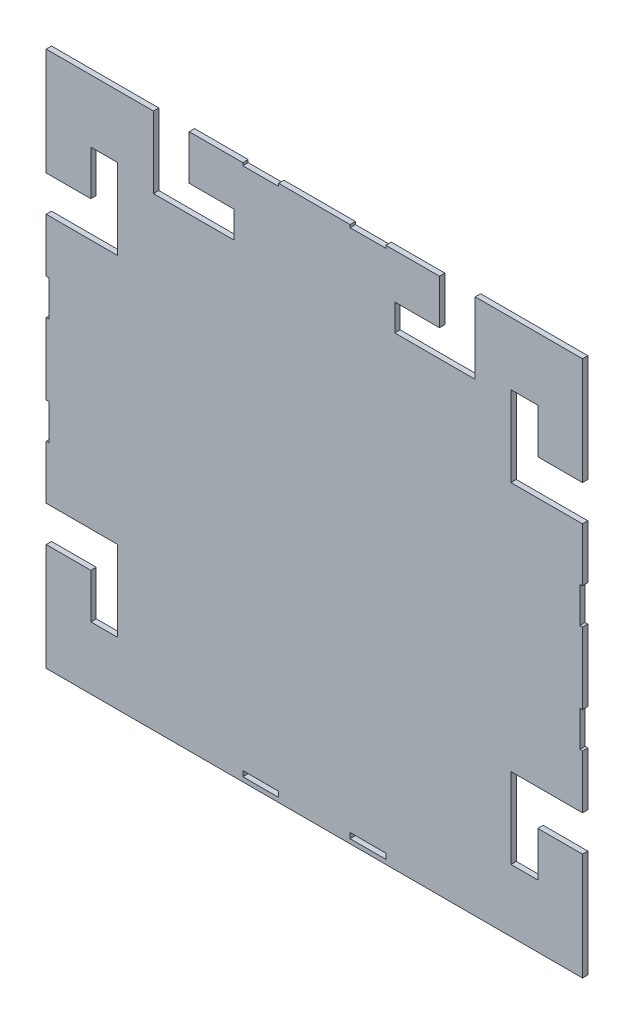
SolidWorks part; units mm, degrees
ref_plane "Plano frontal" through (0, 0, 0) normal (0, 0, 1) x (1, 0, 0)
ref_plane "Plano superior" through (0, 0, 0) normal (0, 1, 0) x (1, 0, 0)
ref_plane "Plano direito" through (0, 0, 0) normal (1, 0, 0) x (0, 0, -1)
sketch "Esboço2" plane through (0, 0, 0) normal (0, 0, 1) x (1, 0, 0)
  line L0 (-63.6451, -170) -> (-63.6451, -110)
  line L1 (-63.6451, -170) -> (236.3549, -170) construction
  line L2 (-63.6451, -170) -> (-63.6451, 130) construction
  line L3 (-63.6451, 130) -> (236.3549, 130) construction
  line L4 (236.3549, -170) -> (236.3549, 130) construction
  line L5 (-63.6451, -110) -> (-38.6451, -110)
  line L6 (-38.6451, -110) -> (-38.6451, -135)
  line L7 (-38.6451, -135) -> (-23.6451, -135)
  line L8 (-23.6451, -135) -> (-23.6451, -90)
  line L9 (-23.6451, -90) -> (-63.6451, -90)
  line L10 (-63.6451, -90) -> (-63.6451, -60)
  line L11 (236.3549, 20) -> (234.8549, 20)
  line L12 (236.3549, 0) -> (234.8549, 0)
  line L13 (234.8549, 0) -> (234.8549, 20)
  line L14 (-63.6451, -40) -> (-63.6451, 0)
  line L15 (236.3549, -40) -> (234.8549, -40)
  line L16 (236.3549, -60) -> (234.8549, -60)
  line L17 (234.8549, -60) -> (234.8549, -40)
  line L18 (-63.6451, 20) -> (-63.6451, 50)
  line L19 (-63.6451, 50) -> (-23.6451, 50)
  line L20 (-23.6451, 50) -> (-23.6451, 95)
  line L21 (-23.6451, 95) -> (-38.6451, 95)
  line L22 (-38.6451, 95) -> (-38.6451, 70)
  line L23 (-38.6451, 70) -> (-63.6451, 70)
  line L24 (-63.6451, 70) -> (-63.6451, 130)
  line L25 (-63.6451, 130) -> (-3.6451, 130)
  line L26 (176.3549, 130) -> (176.3549, 90)
  line L27 (176.3549, 90) -> (131.3549, 90)
  line L28 (131.3549, 90) -> (131.3549, 105)
  line L29 (156.3549, 130) -> (156.3549, 105)
  line L30 (156.3549, 105) -> (131.3549, 105)
  line L31 (16.3549, 130) -> (46.3549, 130)
  line L32 (16.3549, 130) -> (16.3549, 105)
  line L33 (16.3549, 105) -> (41.3549, 105)
  line L34 (41.3549, 105) -> (41.3549, 90)
  line L35 (41.3549, 90) -> (-3.6451, 90)
  line L36 (-3.6451, 90) -> (-3.6451, 130)
  line L37 (176.3549, 130) -> (236.3549, 130)
  line L38 (236.3549, 130) -> (236.3549, 70)
  line L39 (236.3549, 70) -> (211.3549, 70)
  line L40 (211.3549, 70) -> (211.3549, 95)
  line L41 (211.3549, 95) -> (196.3549, 95)
  line L42 (196.3549, 95) -> (196.3549, 50)
  line L43 (196.3549, 50) -> (236.3549, 50)
  line L44 (236.3549, 50) -> (236.3549, 20)
  line L45 (-63.6451, -60) -> (-62.1451, -60)
  line L46 (-62.1451, -60) -> (-62.1451, -40)
  line L47 (-63.6451, -40) -> (-62.1451, -40)
  line L48 (236.3549, 0) -> (236.3549, -40)
  line L49 (-63.6451, 0) -> (-62.1451, 0)
  line L50 (-62.1451, 0) -> (-62.1451, 20)
  line L51 (-62.1451, 20) -> (-63.6451, 20)
  line L52 (236.3549, -60) -> (236.3549, -90)
  line L53 (236.3549, -90) -> (196.3549, -90)
  line L54 (196.3549, -90) -> (196.3549, -135)
  line L55 (196.3549, -135) -> (211.3549, -135)
  line L56 (211.3549, -135) -> (211.3549, -110)
  line L57 (211.3549, -110) -> (236.3549, -110)
  line L58 (236.3549, -110) -> (236.3549, -170)
  line L59 (236.3549, -170) -> (-63.6451, -170)
  line L60 (126.3549, 130) -> (126.3549, 128.5)
  line L61 (126.3549, 128.5) -> (106.3549, 128.5)
  line L62 (106.3549, 128.5) -> (106.3549, 130)
  line L63 (66.3549, 130) -> (106.3549, 130)
  line L64 (66.3549, 130) -> (66.3549, 128.5)
  line L65 (66.3549, 128.5) -> (46.3549, 128.5)
  line L66 (46.3549, 128.5) -> (46.3549, 130)
  line L67 (126.3549, 130) -> (156.3549, 130)
  line L69 (46.3549, -167.5) -> (66.3549, -167.5)
  line L70 (46.3549, -167.5) -> (46.3549, -164.5)
  line L71 (46.3549, -164.5) -> (66.3549, -164.5)
  line L72 (66.3549, -167.5) -> (66.3549, -164.5)
  line L73 (106.3549, -167.5) -> (126.3549, -167.5)
  line L74 (106.3549, -167.5) -> (106.3549, -164.5)
  line L75 (106.3549, -164.5) -> (126.3549, -164.5)
  line L76 (126.3549, -167.5) -> (126.3549, -164.5)
  dimension "D1" = 300
  dimension "D2" = 300
  dimension "D3" = 60
  dimension "D4" = 60
  dimension "D5" = 60
  dimension "D6" = 25
  dimension "D7" = 25
  dimension "D8" = 45
  dimension "D9" = 45
  dimension "D10" = 30
  dimension "D11" = 30
  dimension "D12" = 1.5
  dimension "D13" = 20
  dimension "D14" = 40
  dimension "D15" = 1.5
  dimension "D16" = 60
  dimension "D17" = 40
  dimension "D18" = 45
  dimension "D19" = 15
  dimension "D20" = 25
  dimension "D21" = 25
  dimension "D22" = 15
  dimension "D23" = 45
  dimension "D24" = 1.5
  dimension "D25" = 1.5
  dimension "D26" = 40
  dimension "D27" = 20
  dimension "D28" = 1.5
  dimension "D29" = 300
  dimension "D30" = 45
  dimension "D31" = 60
  dimension "D32" = 30
  dimension "D33" = 45
  dimension "D34" = 25
  dimension "D35" = 25
  dimension "D36" = 40
  dimension "D37" = 40
  dimension "D38" = 40
  dimension "D39" = 40
  dimension "D40" = 1.5
  dimension "D41" = 1.5
  dimension "D44" = 25
  dimension "D45" = 30
  dimension "D47" = 40
  dimension "D50" = 15
  dimension "D51" = 25
  dimension "D52" = 110
  dimension "D53" = 110
  dimension "D54" = 20
  dimension "D55" = 20
  dimension "D56" = 3
  dimension "D57" = 2.5
  dimension "D58" = 2.5
  dimension "D59" = 3
extrude "Ressalto-extrusão1" add sketch "Esboço2" along normal blind 3
